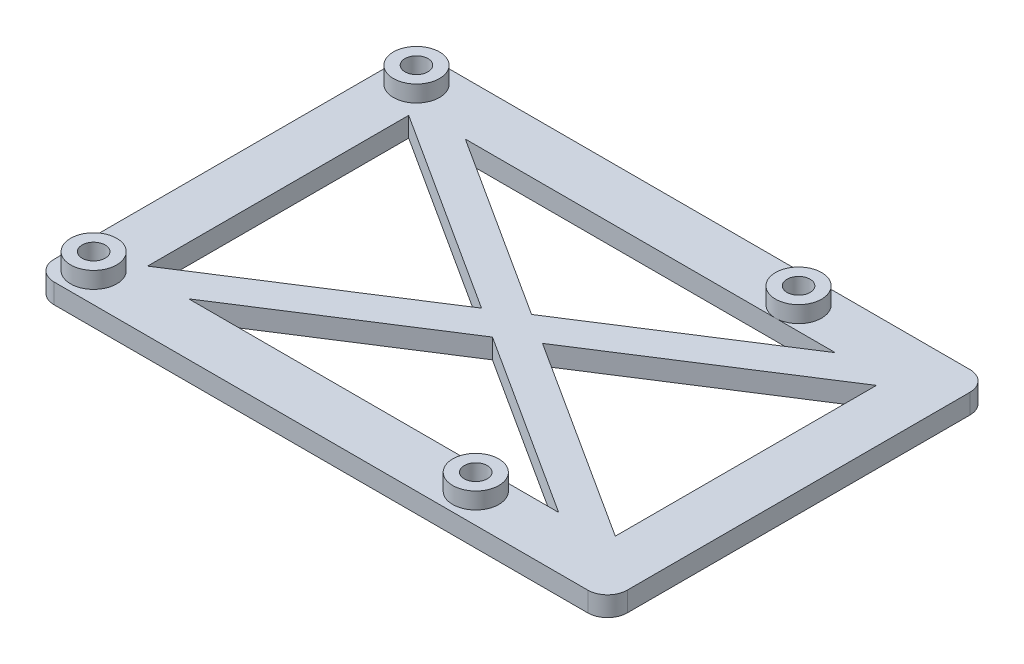
SolidWorks part; units mm, degrees
material "Acrílico (Impacto medio-alto)"
ref_plane "Alzado" through (0, 0, 0) normal (0, 0, 1) x (1, 0, 0)
ref_plane "Planta" through (0, 0, 0) normal (0, 1, 0) x (1, 0, 0)
ref_plane "Vista lateral" through (0, 0, 0) normal (1, 0, 0) x (0, 0, -1)
sketch "Croquis1" plane through (0, 0, 0) normal (0, 1, 0) x (1, 0, 0)
  line L1 (43.5, -29) -> (-43.5, -29)
  line L2 (43.5, -29) -> (43.5, 29)
  line L3 (43.5, 29) -> (-43.5, 29)
  line L4 (-43.5, -29) -> (-43.5, 29)
  line L5 (43.5, -29) -> (-43.5, 29) construction
  line L6 (43.5, 29) -> (-43.5, -29) construction
  point P0 (0, 0)
  dimension "D1" = 87
  dimension "D2" = 58
extrude "Saliente-Extruir1" add sketch "Croquis1" along normal blind 3
sketch "Croquis2" plane through (0, 0, 0) normal (0, -1, 0) x (1, 0, 0)
  circle A0 centre (-39, -24.5) radius 1.75
  circle A1 centre (-39, 24.5) radius 1.75
  circle A2 centre (19, 24.5) radius 1.75
  circle A3 centre (19, -24.5) radius 1.75
  dimension "D1" = 3.5
extrude "Cortar-Extruir1" cut sketch "Croquis2" against normal through all
sketch "Croquis3" plane through (0, 3, 0) normal (0, 1, 0) x (1, 0, 0)
  circle A0 centre (-39, 24.5) radius 3.5
  circle A1 centre (-39, 24.5) radius 1.75 construction
  circle A2 centre (-39, 24.5) radius 1.75
  circle A3 centre (19, 24.5) radius 3.5
  circle A4 centre (19, 24.5) radius 1.75 construction
  circle A5 centre (19, 24.5) radius 1.75
  dimension "D1" = 7
extrude "Saliente-Extruir2" add sketch "Croquis3" along normal blind 2.5
mirror "Simetría1" about plane through (0, 0, 0) normal (0, 0, 1) of "Saliente-Extruir2"
fillet "Redondeo1" radius 3 4 edges at (-43.5, 1.5, -29) (-43.5, 1.5, 29) (43.5, 1.5, 29) (43.5, 1.5, -29)
sketch "Croquis4" plane through (0, 0, 0) normal (0, -1, 0) x (1, 0, 0)
  line L0 (-40.5, 26) -> (40.5, -26) construction
  line L1 (40.5, 26) -> (-40.5, -26) construction
  line L2 (-40.5, 29) -> (40.5, 29) construction
  line L3 (28.0839, 21) -> (0, 2.9708)
  line L4 (-28.0839, 21) -> (0, 2.9708)
  line L5 (35.5, 19.8193) -> (35.5, -19.8193)
  line L6 (35.5, 19.8193) -> (4.6276, 0)
  line L7 (39.1494, 28.1038) -> (-41.8506, -23.8962) construction
  line L8 (43.5, 26) -> (43.5, -26) construction
  line L10 (0, -2.9708) -> (-28.0839, -21)
  line L11 (-35.5, -26) -> (-35.5, 26)
  line L12 (-35.5, -19.8193) -> (-35.5, 19.8193)
  line L13 (4.6276, 0) -> (35.5, -19.8193)
  line L14 (40.5, -21) -> (-40.5, -21)
  line L15 (28.0839, -21) -> (-28.0839, -21)
  line L16 (-39.1494, 28.1038) -> (41.8506, -23.8962) construction
  line L17 (-4.6276, 0) -> (-35.5, -19.8193)
  line L18 (0, -2.9708) -> (28.0839, -21)
  line L20 (-35.5, 19.8193) -> (-4.6276, 0)
  line L22 (-28.0839, 21) -> (28.0839, 21)
  dimension "D3" = 8
  dimension "D6" = 5
  dimension "D7" = 5
  dimension "D8" = 8
  dimension "D1" = 2.5
  dimension "D2" = 2.5
  dimension "D4" = 8
  dimension "D5" = 8
extrude "Cortar-Extruir2" cut sketch "Croquis4" against normal through all
